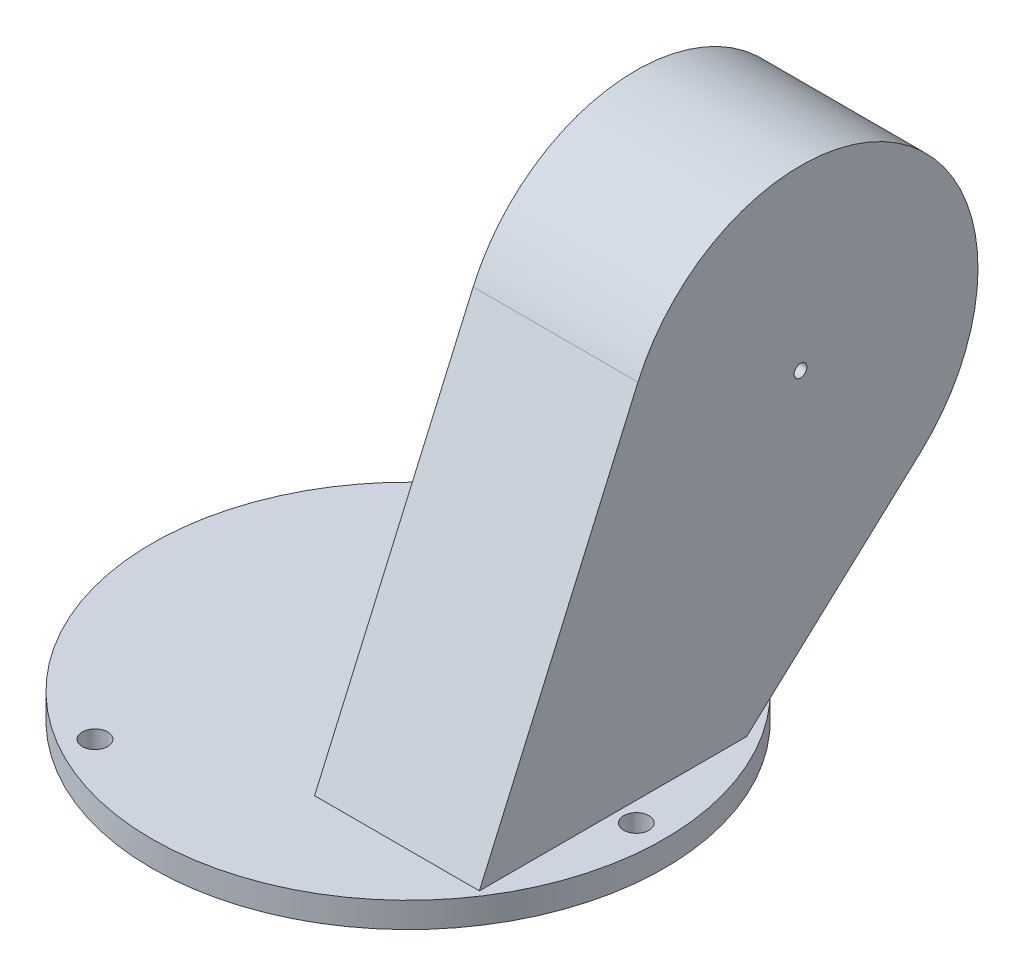
SolidWorks part; units mm, degrees
ref_plane "前视基准面" through (0, 0, 0) normal (0, 0, 1) x (1, 0, 0)
ref_plane "上视基准面" through (0, 0, 0) normal (0, 1, 0) x (1, 0, 0)
ref_plane "右视基准面" through (0, 0, 0) normal (1, 0, 0) x (0, 0, -1)
other "Configuration Table"
sketch "草图1" plane through (0, 0, 0) normal (0, 1, 0) x (1, 0, 0)
  circle A0 centre (0, 0) radius 101
  dimension "D1" = 202
extrude "凸台-拉伸1" add sketch "草图1" along normal blind 10
ref_plane "基准面1" through (0, 10, 0) normal (0, 1, 0) x (1, 0, 0)
sketch "草图2" plane through (0, 10, 0) normal (0, 1, 0) x (1, 0, 0)
  line L0 (0, 0) -> (101, 0) construction
  circle A0 centre (0, 0) radius 101 construction
  circle A1 centre (90, 0) radius 5
  dimension "D2" = 10
  dimension "D1" = 90
extrude "切除-拉伸1" cut sketch "草图2" against normal through all
cosmetic thread "装饰螺纹线3" parameters "D2"=11
pattern_circular "阵列(圆周)1" count 3 over 360 about axis through (-0.2211, 0, 0) along (0, 1, 0) of "切除-拉伸1"
cosmetic thread "装饰螺纹线1" parameters "D2"=11
cosmetic thread "装饰螺纹线2" parameters "D2"=11
sketch "草图4" plane through (0, 10, 0) normal (0, 1, 0) x (1, 0, 0)
  line L0 (0, 0) -> (101, 0) construction
  line L2 (97.239, 1.9207) -> (99.4153, 1.9207)
  line L3 (97.239, 1.9207) -> (97.239, -1.9657)
  line L4 (97.239, -1.9657) -> (99.4153, -1.9657)
  line L5 (99.4153, 1.9207) -> (99.4153, -1.9657)
  circle A0 centre (0, 0) radius 101 construction
extrude "凸台-拉伸2" add sketch "草图4" along normal blind 10
ref_plane "基准面2" through (82.239, 0, 0) normal (-1, 0, 0) x (0, 0, 1)
sketch "草图5" plane through (82.239, 0, 0) normal (-1, 0, 0) x (0, 0, 1)
  line L0 (-119.7709, 72.7054) -> (-51.2501, 10)
  line L5 (-8.417, 152.482) -> (54.1282, 10)
  line L7 (101, 10) -> (-101, 10) construction
  line L8 (111.1, 10) -> (-111.1, 10) construction
  line L9 (-51.2501, 10) -> (54.1282, 10)
  arc A0 (-8.417, 152.482) -> (-119.7709, 72.7054) centre (-72.5134, 124.3457) ccw
  dimension "D1" = 140
extrude "凸台-拉伸3" add sketch "草图5" along normal blind 65
ref_plane "基准面3" through (17.239, 0, 0) normal (-1, 0, 0) x (0, 0, 1)
sketch "草图6" plane through (17.239, 0, 0) normal (-1, 0, 0) x (0, 0, 1)
  line L0 (-113.2806, 181.2495) -> (-48.6731, 91.0689) construction
  line L1 (-14.5382, 163.5743) -> (-72.5134, 124.3457) construction
  arc A0 (-8.417, 152.482) -> (-119.7709, 72.7054) centre (-72.5134, 124.3457) ccw construction
  circle A1 centre (-72.5134, 124.3457) radius 2.5
  dimension "D1" = 5
extrude "切除-拉伸2" cut sketch "草图6" against normal up to next
cosmetic thread "装饰螺纹线4" parameters "D2"=6
sketch "草图7" plane through (17.239, 0, 0) normal (-1, 0, 0) x (0, 0, 1)
  circle A0 centre (-72.5134, 124.3457) radius 15
  dimension "D1" = 30
extrude "凸台-拉伸4" add sketch "草图7" along normal blind 3
sketch "草图8" plane through (14.239, 0, 0) normal (-1, 0, 0) x (0, 0, 1)
  circle A0 centre (-72.5134, 124.3457) radius 2.5
  dimension "D1" = 5
extrude "切除-拉伸3" cut sketch "草图8" against normal blind 3
sketch "草图9" plane through (99.4153, 0, 0) normal (1, 0, 0) x (0, 0, -1)
  line L0 (111.1, 10) -> (-111.1, 10) construction
  line L1 (-3.0096, 20.7642) -> (3.5337, 20.7642)
  line L2 (-3.0096, 20.7642) -> (-3.0096, 10)
  line L3 (-3.0096, 10) -> (3.5337, 10)
  line L4 (3.5337, 20.7642) -> (3.5337, 10)
extrude "切除-拉伸4" cut sketch "草图9" against normal blind 10
